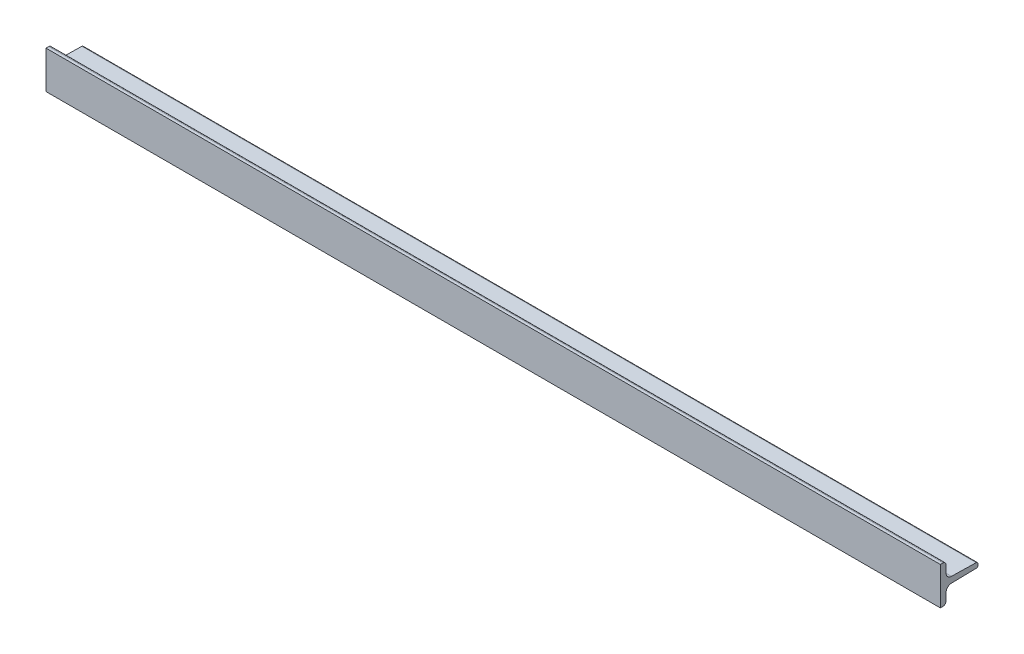
SolidWorks part; units mm, degrees
ref_plane "Front Plane" through (0, 0, 0) normal (0, 0, 1) x (1, 0, 0)
ref_plane "Top Plane" through (0, 0, 0) normal (0, 1, 0) x (1, 0, 0)
ref_plane "Right Plane" through (0, 0, 0) normal (1, 0, 0) x (0, 0, -1)
sketch "Sketch1" plane through (0, 0, 0) normal (0, 0, 1) x (1, 0, 0)
  line L0 (0, 0) -> (475, 0)
  point P4 (0, 0)
  dimension "D1" = 475
other "T section T 20 X 20(1)"
ref_plane "Plane1" through (0, 0, 0) normal (1, 0, 0) x (0, 1, 0)
sketch "Sketch12" plane through (0, 0, 0) normal (1, 0, 0) x (0, 1, 0)
  line L0 (-10, 20) -> (10, 20)
  line L2 (-1.3196, 0.98) -> (-1.581, 14.051)
  line L3 (-4.5204, 16.9904) -> (-8.53, 17.0706)
  line L5 (-10, 20) -> (-10, 18.5703)
  line L6 (10, 20) -> (10, 18.5703)
  line L7 (8.53, 17.0706) -> (4.5204, 16.9904)
  line L8 (1.581, 14.051) -> (1.3196, 0.98)
  line L9 (-5, 17) -> (5, 17) construction
  line L10 (0, 20) -> (0, 0) construction
  line L12 (-0.3198, 0) -> (0.3198, 0)
  arc A0 (-8.53, 17.0706) -> (-10, 18.5703) centre (-8.5, 18.5703) cw
  arc A1 (8.53, 17.0706) -> (10, 18.5703) centre (8.5, 18.5703) ccw
  arc A2 (-1.581, 14.051) -> (-4.5204, 16.9904) centre (-4.5804, 13.991) ccw
  arc A3 (4.5204, 16.9904) -> (1.581, 14.051) centre (4.5804, 13.991) ccw
  arc A4 (-0.3198, 0) -> (-1.3196, 0.98) centre (-0.3198, 1) cw
  arc A5 (1.3196, 0.98) -> (0.3198, 0) centre (0.3198, 1) cw
  point P16 (10, 17.1)
  point P24 (-1.3, 0)
  point P27 (1.3, 0)
  point P28 (0, 0)
  dimension "D2" = 1.146
  dimension "R2" = 1.5
  dimension "R1" = 3
  dimension "R3" = 1
  dimension "D1" = 1.146
  dimension "D3" = 2.9
  dimension "BF" = 20
  dimension "DEPTH" = 20
  dimension "TF" = 3
  dimension "D4" = 2.5999
  dimension "D5" = 1.146
